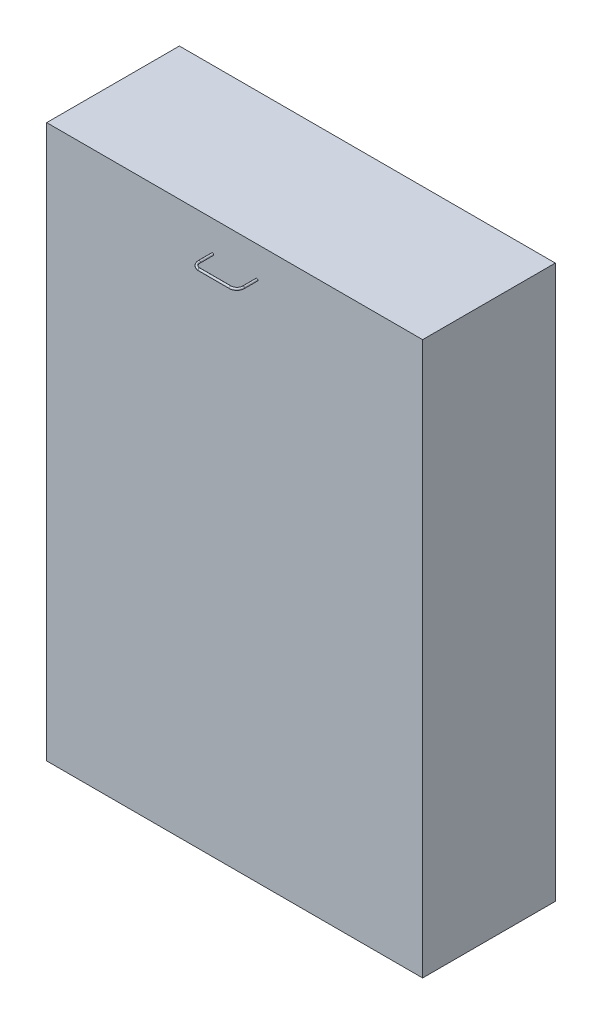
SolidWorks part; units mm, degrees
ref_plane "Alzado" through (0, 0, 0) normal (0, 0, 1) x (1, 0, 0)
ref_plane "Planta" through (0, 0, 0) normal (0, 1, 0) x (1, 0, 0)
ref_plane "Vista lateral" through (0, 0, 0) normal (1, 0, 0) x (0, 0, -1)
sketch "Croquis1" plane through (0, 0, 0) normal (0, 0, 1) x (1, 0, 0)
  line L1 (-425, 70) -> (425, 70)
  line L2 (-425, 70) -> (-425, -1180)
  line L3 (-425, -1180) -> (425, -1180)
  line L4 (425, 70) -> (425, -1180)
  line L5 (-425, 70) -> (425, -1180) construction
  line L6 (-425, -1180) -> (425, 70) construction
  point P0 (0, -555)
  point P5 (0, 70)
  dimension "D1" = 850
  dimension "D2" = 1250
  dimension "D3" = 70
extrude "Saliente-Extruir1" add sketch "Croquis1" along normal blind 300
sketch "Croquis2" plane through (0, 0, 0) normal (0, 1, 0) x (1, 0, 0)
  line L0 (-50, -300) -> (-50, -330)
  line L1 (425, -300) -> (-425, -300) construction
  line L2 (-35, -345) -> (35, -345)
  line L3 (50, -330) -> (50, -300)
  arc A0 (-50, -330) -> (-35, -345) centre (-35, -330) ccw
  arc A1 (35, -345) -> (50, -330) centre (35, -330) ccw
  point P9 (0, -345)
  dimension "D2" = 15
  dimension "D1" = 100
  dimension "D3" = 45
sketch "Croquis3" plane through (0, 0, 300) normal (0, 0, 1) x (1, 0, 0)
  line L0 (-35, 0) -> (-50, 0) construction
  circle A0 centre (-50, 0) radius 2.5
  dimension "D1" = 5
sweep "Barrer1" add profiles "Croquis3" path "Croquis2"
